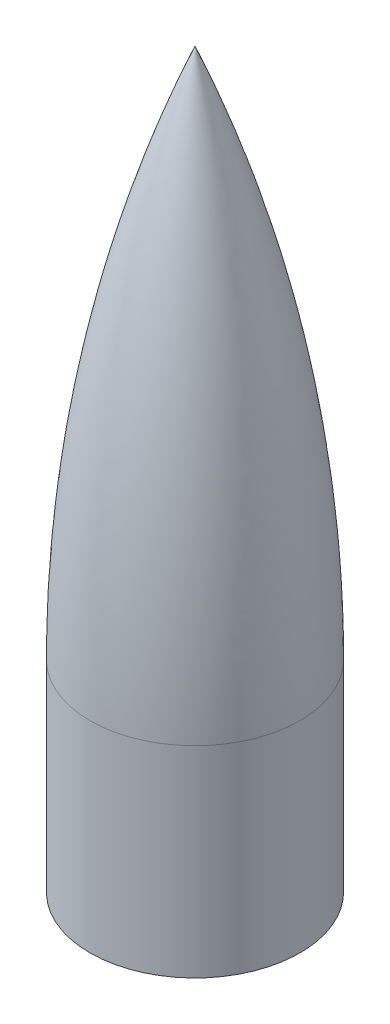
SolidWorks part; units mm, degrees
other "Markup1"
sketch "Sketch4" plane through (78.16, -154.2442, 78.16) normal (0.9651, -0.1718, 0.1975) x (-0.1686, -0.9851, -0.0334)
material "PE High Density Film"
ref_plane "Front Plane" through (0, 0, 0) normal (0, 0, 1) x (1, 0, 0)
ref_plane "Top Plane" through (0, 0, 0) normal (0, 1, 0) x (1, 0, 0)
ref_plane "Right Plane" through (0, 0, 0) normal (1, 0, 0) x (0, 0, -1)
sketch "Sketch1" plane through (0, 0, 0) normal (0, 0, 1) x (1, 0, 0)
  line L3 (0, 0) -> (0, 398.8705) construction
  line L6 (0, 400) -> (0, 402.7567)
  line L9 (0, 400) -> (0, 396.4892)
  line L10 (78.35, 0) -> (-964.0394, 0) construction
  line L11 (0, 411.0234) -> (0, 614.1078) construction
  line L14 (78.35, 0) -> (78.35, -150)
  line L15 (78.35, -150) -> (80.75, -150)
  line L16 (80.75, 0) -> (80.75, -150)
  arc A0 (78.35, 0) -> (0, 396.4892) centre (-964.0394, 0) ccw
  arc A1 (80.75, 0) -> (0, 402.7567) centre (-964.0394, 0) ccw
  circle A2 centre (-964.0394, 0) radius 1042.3894 construction
  circle A3 centre (-964.0394, 0) radius 1044.7894 construction
  point P11 (0, 400)
  dimension "D5" = 1042.3894
  dimension "D1" = 400
  dimension "D2" = 3.5108
  dimension "D3" = 2.4
  dimension "D4" = 78.35
  dimension "D6" = 150
  dimension "D7" = 2.4
revolve "Revolve3" add sketch "Sketch1" angle 360 about L6
sketch "Sketch5" plane through (0, -150, 0) normal (0, -1, 0) x (1, 0, 0)
  circle A0 centre (0, 0) radius 78.35
extrude "Boss-Extrude1" add sketch "Sketch5" against normal up to surface (150 mm away) separate body
delete or keep bodies "Body-Delete/Keep 1" type delete bodies bodies 101
